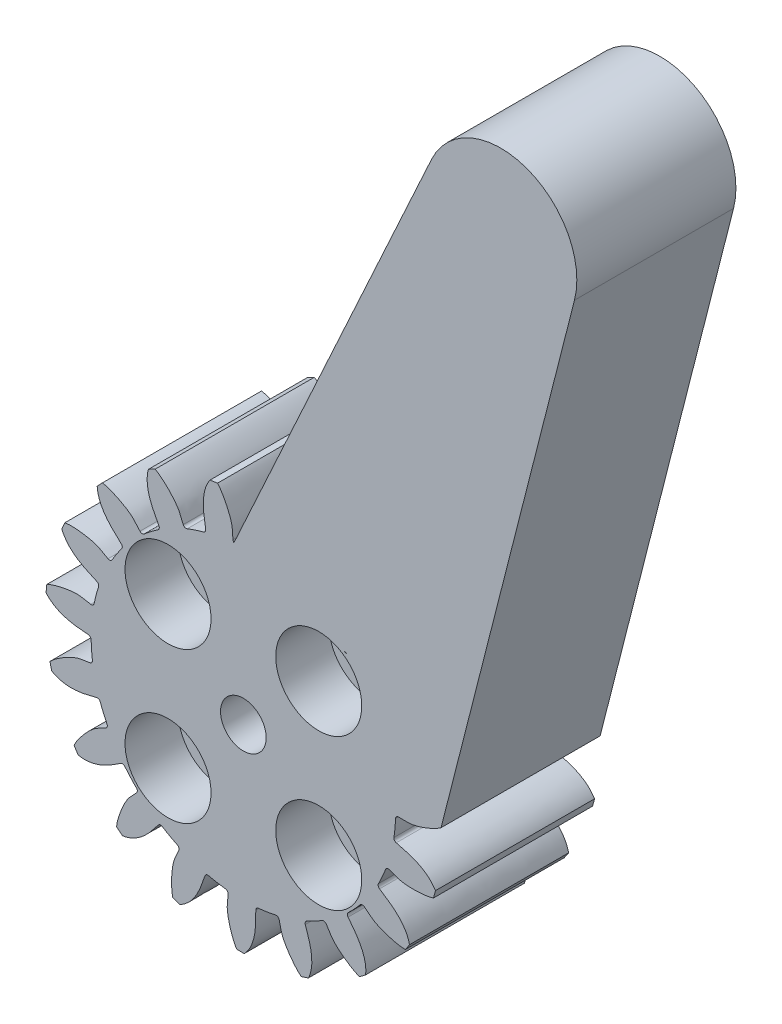
SolidWorks part; units mm, degrees
ref_plane "前视基准面" through (0, 0, 0) normal (0, 0, 1) x (1, 0, 0)
ref_plane "上视基准面" through (0, 0, 0) normal (0, 1, 0) x (1, 0, 0)
ref_plane "右视基准面" through (0, 0, 0) normal (1, 0, 0) x (0, 0, -1)
other "Configuration Table"
sketch "草图3" plane through (0, 0, 0) normal (0, 0, 1) x (1, 0, 0)
  circle A0 centre (0, 0) radius 13
  circle A1 centre (0, 0) radius 10
  dimension "D1" = 26
  dimension "D2" = 20
extrude "凸台-拉伸1" add sketch "草图3" along normal blind 4 contours A1 | A0 A1
sketch "草图6" plane through (0, 0, 4) normal (0, 0, 1) x (1, 0, 0)
  line L0 (0, 14.519) -> (0, -0.3622) construction
  line L5 (0, 0) -> (-1.6968, 12.8888) construction
  line L6 (-1.6968, 12.8888) -> (-1.8736, 14.2316)
  line L7 (-1.8736, 14.2316) -> (3.0009, 14.404)
  line L8 (3.0009, 14.404) -> (2.085, 12.8317)
  arc A0 (0.6559, 9.9785) -> (-0.4764, 9.9886) centre (0, 0) ccw
  circle A1 centre (0, 0) radius 13 construction
  arc A2 (0.6559, 9.9785) -> (0.8668, 10.1484) centre (0.669, 10.178) ccw
  arc A3 (-0.6854, 10.1744) -> (-0.4764, 9.9886) centre (-0.4859, 10.1884) ccw
  spline S0 degree 3 poles (-1.6968, 12.8888) (-1.3404, 12.4914) (-0.7219, 11.2236) (-0.7215, 10.6885) (-0.6854, 10.1744) knots 0 0 0 0 0.644244 0.940775 0.940775 0.940775 0.940775
  spline S1 degree 3 poles (2.085, 12.8317) (1.4718, 12.3854) (1.0735, 11.4242) (0.9081, 10.424) (0.8668, 10.1484) knots 0 0 0 0 0.67612 0.940775 0.940775 0.940775 0.940775
  dimension "D1" = 20
  dimension "D2" = 0.2
  dimension "D3" = 7.5
extrude "切除-拉伸2" cut sketch "草图6" against normal through all both
pattern_circular "阵列(圆周)4" count 19 over 360 about axis through (0, 0, 4) along (0, 0, 1) of "切除-拉伸2"
ref_plane "基准面3" through (0, 0, 2) normal (0, 0, 1) x (1, 0, 0)
sketch "草图8" plane through (0, 0, 0) normal (0, 0, -1) x (-1, 0, 0)
  line L1 (-4.9497, -4.9497) -> (4.9497, -4.9497) construction
  line L2 (-4.9497, -4.9497) -> (-4.9497, 4.9497) construction
  line L3 (-4.9497, 4.9497) -> (4.9497, 4.9497) construction
  line L4 (4.9497, -4.9497) -> (4.9497, 4.9497) construction
  line L5 (-4.9497, -4.9497) -> (4.9497, 4.9497) construction
  line L6 (-4.9497, 4.9497) -> (4.9497, -4.9497) construction
  circle A0 centre (0, 0) radius 1.5
  circle A1 centre (-4.9497, 4.9497) radius 1.5
  circle A2 centre (-4.9497, -4.9497) radius 1.5
  circle A3 centre (4.9497, -4.9497) radius 1.5
  circle A4 centre (4.9497, 4.9497) radius 1.5
  dimension "D1" = 3
  dimension "D3" = 3
  dimension "D4" = 3
  dimension "D5" = 3
  dimension "D6" = 3
  dimension "D2" = 14
extrude "切除-拉伸4" cut sketch "草图8" against normal through all both and the other way through all
sketch "草图13" plane through (0, 0, 0) normal (0, 0, -1) x (-1, 0, 0)
  circle A0 centre (-4.9497, -4.9497) radius 1.5 construction
  circle A1 centre (4.9497, -4.9497) radius 1.5 construction
  circle A2 centre (4.9497, 4.9497) radius 1.5 construction
  circle A3 centre (0, 0) radius 1.5 construction
  circle A4 centre (-4.9497, 4.9497) radius 1.5 construction
  circle A5 centre (-4.9497, -4.9497) radius 1.5
  circle A6 centre (4.9497, -4.9497) radius 1.5
  circle A7 centre (4.9497, 4.9497) radius 1.5
  circle A8 centre (0, 0) radius 1.5
  circle A9 centre (-4.9497, 4.9497) radius 1.5
  arc A61 (2.4754, 9.88) -> (2.6197, 9.6508) centre (2.6721, 9.8438) ccw
  arc A62 (2.4754, 9.88) -> (2.6197, 9.6508) centre (2.6721, 9.8438) ccw
  arc A63 (0.4764, 9.9886) -> (0.6854, 10.1744) centre (0.4859, 10.1884) ccw
  arc A64 (-11.8827, 5.2728) -> (-12.0778, 4.8089) centre (0, 0) ccw
  arc A65 (-12.9509, 1.1288) -> (-12.9849, 0.6267) centre (0, 0) ccw
  arc A66 (-9.9939, -0.3501) -> (-10.1963, -0.1571) centre (-10.1937, -0.3571) ccw
  arc A67 (-9.9939, -0.3501) -> (-9.8902, -1.4776) centre (0, 0) ccw
  arc A68 (-10.0421, -1.7019) -> (-9.8902, -1.4776) centre (-10.088, -1.5072) ccw
  arc A69 (-12.6157, -3.1375) -> (-12.4848, -3.6234) centre (0, 0) ccw
  arc A70 (-9.3387, -3.5761) -> (-9.5928, -3.4593) centre (-9.5255, -3.6476) ccw
  arc A71 (-9.3387, -3.5761) -> (-8.8746, -4.6089) centre (0, 0) ccw
  arc A72 (-8.9454, -4.8703) -> (-8.8746, -4.6089) centre (-9.052, -4.7011) ccw
  arc A73 (-10.9134, -7.0638) -> (-10.6318, -7.4809) centre (0, 0) ccw
  arc A74 (-7.6715, -6.4146) -> (-7.9498, -6.3867) centre (-7.825, -6.5429) ccw
  arc A75 (-7.6715, -6.4146) -> (-6.8972, -7.2408) centre (0, 0) ccw
  arc A76 (-6.8794, -7.511) -> (-6.8972, -7.2408) centre (-7.0351, -7.3856) ccw
  arc A77 (-8.0285, -10.2247) -> (-7.6267, -10.5277) centre (0, 0) ccw
  arc A78 (-5.1731, -8.558) -> (-5.4453, -8.6219) centre (-5.2765, -8.7292) ccw
  arc A79 (-5.1731, -8.558) -> (-4.1724, -9.088) centre (0, 0) ccw
  arc A80 (-4.0678, -9.3378) -> (-4.1724, -9.088) centre (-4.2559, -9.2697) ccw
  arc A81 (-4.2735, -12.2775) -> (-3.7951, -12.4337) centre (0, 0) ccw
  arc A82 (-2.114, -9.774) -> (-2.3508, -9.9228) centre (-2.1563, -9.9695) ccw
  arc A83 (-2.114, -9.774) -> (-0.9955, -9.9503) centre (0, 0) ccw
  arc A84 (-0.8154, -10.1526) -> (-0.9955, -9.9503) centre (-1.0154, -10.1493) ccw
  arc A85 (-0.0555, -12.9999) -> (0.4477, -12.9923) centre (0, 0) ccw
  arc A86 (1.1742, -9.9308) -> (0.9986, -10.1485) centre (1.1976, -10.1294) ccw
  arc A87 (1.1742, -9.9308) -> (2.2893, -9.7344) centre (0, 0) ccw
  arc A88 (2.5253, -9.8673) -> (2.2893, -9.7344) centre (2.3351, -9.9291) ccw
  arc A89 (4.1686, -12.3135) -> (4.6421, -12.143) centre (0, 0) ccw
  arc A90 (4.3351, -9.0115) -> (4.2397, -9.2744) centre (4.4218, -9.1917) ccw
  arc A91 (4.3351, -9.0115) -> (5.326, -8.4636) centre (0, 0) ccw
  arc A92 (5.5924, -8.5127) -> (5.326, -8.4636) centre (5.4326, -8.6329) ccw
  arc A93 (7.9409, -10.2928) -> (8.3333, -9.9777) centre (0, 0) ccw
  arc A94 (7.0262, -7.1156) -> (7.0213, -7.3953) centre (7.1667, -7.2579) ccw
  arc A95 (7.0262, -7.1156) -> (7.7856, -6.2757) centre (0, 0) ccw
  arc A96 (8.0535, -6.2356) -> (7.7856, -6.2757) centre (7.9413, -6.4012) ccw
  arc A97 (10.8527, -7.1567) -> (11.1216, -6.7313) centre (0, 0) ccw
  arc A98 (8.956, -4.4487) -> (9.0421, -4.7147) centre (9.1351, -4.5376) ccw
  arc A99 (8.956, -4.4487) -> (9.4015, -3.4077) centre (0, 0) ccw
  arc A100 (9.6418, -3.2828) -> (9.4015, -3.4077) centre (9.5895, -3.4758) ccw
  arc A101 (12.5885, -3.2451) -> (12.7046, -2.7554) centre (0, 0) ccw
  arc A102 (9.9152, -1.2996) -> (10.0831, -1.5233) centre (10.1135, -1.3256) ccw
  arc A103 (9.9152, -1.2996) -> (9.9985, -0.1704) centre (0, 0) ccw
  arc A104 (10.1853, 0.0258) -> (9.9985, -0.1704) centre (10.1985, -0.1738) ccw
  arc A105 (12.9601, 1.0182) -> (12.9109, 1.5191) centre (0, 0) ccw
  arc A106 (9.7999, 1.9902) -> (10.0314, 1.8332) centre (9.9959, 2.03) ccw
  arc A107 (9.7999, 1.9902) -> (9.5121, 3.0854) centre (0, 0) ccw
  arc A108 (9.6251, 3.3315) -> (9.5121, 3.0854) centre (9.7024, 3.1471) ccw
  arc A109 (11.9272, 5.1712) -> (11.7181, 5.629) centre (0, 0) ccw
  arc A110 (8.6227, 5.0644) -> (8.8926, 4.9911) centre (8.7952, 5.1657) ccw
  arc A111 (8.6227, 5.0644) -> (7.9949, 6.0068) centre (0, 0) ccw
  arc A112 (8.0218, 6.2763) -> (7.9949, 6.0068) centre (8.1548, 6.1269) ccw
  arc A113 (9.6019, 8.7638) -> (9.2555, 9.1288) centre (0, 0) ccw
  arc A114 (6.5111, 7.5898) -> (6.7902, 7.608) centre (6.6413, 7.7416) ccw
  arc A115 (6.5111, 7.5898) -> (5.6113, 8.2773) centre (0, 0) ccw
  arc A116 (5.5493, 8.5409) -> (5.6113, 8.2773) centre (5.7236, 8.4428) ccw
  arc A117 (6.236, 11.4067) -> (5.7899, 11.6395) centre (0, 0) ccw
  arc A118 (3.6939, 9.2927) -> (3.9519, 9.4006) centre (3.7678, 9.4786) ccw
  arc A119 (3.6939, 9.2927) -> (2.6197, 9.6508) centre (0, 0) ccw
  arc A120 (2.1944, 12.8134) -> (1.6968, 12.8888) centre (0, 0) ccw
  arc A121 (0.4764, 9.9886) -> (0.6854, 10.1744) centre (0.4859, 10.1884) ccw
  arc A125 (-11.8827, 5.2728) -> (-12.0778, 4.8089) centre (0, 0) ccw
  arc A126 (-12.9509, 1.1288) -> (-12.9849, 0.6267) centre (0, 0) ccw
  arc A127 (-9.9939, -0.3501) -> (-10.1963, -0.1571) centre (-10.1937, -0.3571) ccw
  arc A128 (-9.9939, -0.3501) -> (-9.8902, -1.4776) centre (0, 0) ccw
  arc A129 (-10.0421, -1.7019) -> (-9.8902, -1.4776) centre (-10.088, -1.5072) ccw
  arc A130 (-12.6157, -3.1375) -> (-12.4848, -3.6234) centre (0, 0) ccw
  arc A131 (-9.3387, -3.5761) -> (-9.5928, -3.4593) centre (-9.5255, -3.6476) ccw
  arc A132 (-9.3387, -3.5761) -> (-8.8746, -4.6089) centre (0, 0) ccw
  arc A133 (-8.9454, -4.8703) -> (-8.8746, -4.6089) centre (-9.052, -4.7011) ccw
  arc A134 (-10.9134, -7.0638) -> (-10.6318, -7.4809) centre (0, 0) ccw
  arc A135 (-7.6715, -6.4146) -> (-7.9498, -6.3867) centre (-7.825, -6.5429) ccw
  arc A136 (-7.6715, -6.4146) -> (-6.8972, -7.2408) centre (0, 0) ccw
  arc A137 (-6.8794, -7.511) -> (-6.8972, -7.2408) centre (-7.0351, -7.3856) ccw
  arc A138 (-8.0285, -10.2247) -> (-7.6267, -10.5277) centre (0, 0) ccw
  arc A139 (-5.1731, -8.558) -> (-5.4453, -8.6219) centre (-5.2765, -8.7292) ccw
  arc A140 (-5.1731, -8.558) -> (-4.1724, -9.088) centre (0, 0) ccw
  arc A141 (-4.0678, -9.3378) -> (-4.1724, -9.088) centre (-4.2559, -9.2697) ccw
  arc A142 (-4.2735, -12.2775) -> (-3.7951, -12.4337) centre (0, 0) ccw
  arc A143 (-2.114, -9.774) -> (-2.3508, -9.9228) centre (-2.1563, -9.9695) ccw
  arc A144 (-2.114, -9.774) -> (-0.9955, -9.9503) centre (0, 0) ccw
  arc A145 (-0.8154, -10.1526) -> (-0.9955, -9.9503) centre (-1.0154, -10.1493) ccw
  arc A146 (-0.0555, -12.9999) -> (0.4477, -12.9923) centre (0, 0) ccw
  arc A147 (1.1742, -9.9308) -> (0.9986, -10.1485) centre (1.1976, -10.1294) ccw
  arc A148 (1.1742, -9.9308) -> (2.2893, -9.7344) centre (0, 0) ccw
  arc A149 (2.5253, -9.8673) -> (2.2893, -9.7344) centre (2.3351, -9.9291) ccw
  arc A150 (4.1686, -12.3135) -> (4.6421, -12.143) centre (0, 0) ccw
  arc A151 (4.3351, -9.0115) -> (4.2397, -9.2744) centre (4.4218, -9.1917) ccw
  arc A152 (4.3351, -9.0115) -> (5.326, -8.4636) centre (0, 0) ccw
  arc A153 (5.5924, -8.5127) -> (5.326, -8.4636) centre (5.4326, -8.6329) ccw
  arc A154 (7.9409, -10.2928) -> (8.3333, -9.9777) centre (0, 0) ccw
  arc A155 (7.0262, -7.1156) -> (7.0213, -7.3953) centre (7.1667, -7.2579) ccw
  arc A156 (7.0262, -7.1156) -> (7.7856, -6.2757) centre (0, 0) ccw
  arc A157 (8.0535, -6.2356) -> (7.7856, -6.2757) centre (7.9413, -6.4012) ccw
  arc A158 (10.8527, -7.1567) -> (11.1216, -6.7313) centre (0, 0) ccw
  arc A159 (8.956, -4.4487) -> (9.0421, -4.7147) centre (9.1351, -4.5376) ccw
  arc A160 (8.956, -4.4487) -> (9.4015, -3.4077) centre (0, 0) ccw
  arc A161 (9.6418, -3.2828) -> (9.4015, -3.4077) centre (9.5895, -3.4758) ccw
  arc A162 (12.5885, -3.2451) -> (12.7046, -2.7554) centre (0, 0) ccw
  arc A163 (9.9152, -1.2996) -> (10.0831, -1.5233) centre (10.1135, -1.3256) ccw
  arc A164 (9.9152, -1.2996) -> (9.9985, -0.1704) centre (0, 0) ccw
  arc A165 (10.1853, 0.0258) -> (9.9985, -0.1704) centre (10.1985, -0.1738) ccw
  arc A166 (12.9601, 1.0182) -> (12.9109, 1.5191) centre (0, 0) ccw
  arc A167 (9.7999, 1.9902) -> (10.0314, 1.8332) centre (9.9959, 2.03) ccw
  arc A168 (9.7999, 1.9902) -> (9.5121, 3.0854) centre (0, 0) ccw
  arc A169 (9.6251, 3.3315) -> (9.5121, 3.0854) centre (9.7024, 3.1471) ccw
  arc A170 (11.9272, 5.1712) -> (11.7181, 5.629) centre (0, 0) ccw
  arc A171 (8.6227, 5.0644) -> (8.8926, 4.9911) centre (8.7952, 5.1657) ccw
  arc A172 (8.6227, 5.0644) -> (7.9949, 6.0068) centre (0, 0) ccw
  arc A173 (8.0218, 6.2763) -> (7.9949, 6.0068) centre (8.1548, 6.1269) ccw
  arc A174 (9.6019, 8.7638) -> (9.2555, 9.1288) centre (0, 0) ccw
  arc A175 (6.5111, 7.5898) -> (6.7902, 7.608) centre (6.6413, 7.7416) ccw
  arc A176 (6.5111, 7.5898) -> (5.6113, 8.2773) centre (0, 0) ccw
  arc A177 (5.5493, 8.5409) -> (5.6113, 8.2773) centre (5.7236, 8.4428) ccw
  arc A178 (6.236, 11.4067) -> (5.7899, 11.6395) centre (0, 0) ccw
  arc A179 (3.6939, 9.2927) -> (3.9519, 9.4006) centre (3.7678, 9.4786) ccw
  arc A180 (3.6939, 9.2927) -> (2.6197, 9.6508) centre (0, 0) ccw
  arc A181 (2.1944, 12.8134) -> (1.6968, 12.8888) centre (0, 0) ccw
  arc A192 (0.4764, 9.9886) -> (-0.6559, 9.9785) centre (0, 0) ccw
  arc A193 (0.4764, 9.9886) -> (-0.6559, 9.9785) centre (0, 0) ccw
  arc A210 (-0.8668, 10.1484) -> (-0.6559, 9.9785) centre (-0.669, 10.178) ccw
  arc A211 (-0.8668, 10.1484) -> (-0.6559, 9.9785) centre (-0.669, 10.178) ccw
  arc A212 (-2.085, 12.8317) -> (-2.5801, 12.7414) centre (0, 0) ccw
  arc A213 (-2.085, 12.8317) -> (-2.5801, 12.7414) centre (0, 0) ccw
  arc A214 (-2.7927, 9.6021) -> (-2.6553, 9.8457) centre (-2.8486, 9.7942) ccw
  arc A215 (-2.7927, 9.6021) -> (-2.6553, 9.8457) centre (-2.8486, 9.7942) ccw
  arc A216 (-2.7927, 9.6021) -> (-3.8603, 9.2248) centre (0, 0) ccw
  arc A217 (-2.7927, 9.6021) -> (-3.8603, 9.2248) centre (0, 0) ccw
  arc A218 (-4.115, 9.3171) -> (-3.8603, 9.2248) centre (-3.9375, 9.4093) ccw
  arc A219 (-4.115, 9.3171) -> (-3.8603, 9.2248) centre (-3.9375, 9.4093) ccw
  arc A220 (-6.1385, 11.4595) -> (-6.5774, 11.2133) centre (0, 0) ccw
  arc A221 (-6.1385, 11.4595) -> (-6.5774, 11.2133) centre (0, 0) ccw
  arc A222 (-5.7592, 8.1751) -> (-5.7084, 8.4501) centre (-5.8744, 8.3386) ccw
  arc A223 (-5.7592, 8.1751) -> (-5.7084, 8.4501) centre (-5.8744, 8.3386) ccw
  arc A224 (-5.7592, 8.1751) -> (-6.6465, 7.4716) centre (0, 0) ccw
  arc A225 (-5.7592, 8.1751) -> (-6.6465, 7.4716) centre (0, 0) ccw
  arc A226 (-6.9173, 7.4761) -> (-6.6465, 7.4716) centre (-6.7794, 7.621) ccw
  arc A227 (-6.9173, 7.4761) -> (-6.6465, 7.4716) centre (-6.7794, 7.621) ccw
  arc A228 (-9.5268, 8.8454) -> (-9.862, 8.47) centre (0, 0) ccw
  arc A229 (-9.5268, 8.8454) -> (-9.862, 8.47) centre (0, 0) ccw
  arc A230 (-8.1016, 5.8621) -> (-8.1428, 6.1387) centre (-8.2636, 5.9793) ccw
  arc A231 (-8.1016, 5.8621) -> (-8.1428, 6.1387) centre (-8.2636, 5.9793) ccw
  arc A232 (-8.1016, 5.8621) -> (-8.7124, 4.9086) centre (0, 0) ccw
  arc A233 (-8.1016, 5.8621) -> (-8.7124, 4.9086) centre (0, 0) ccw
  arc A234 (-8.97, 4.825) -> (-8.7124, 4.9086) centre (-8.8866, 5.0068) ccw
  arc A235 (-8.97, 4.825) -> (-8.7124, 4.9086) centre (-8.8866, 5.0068) ccw
  arc A236 (-9.566, 2.9139) -> (-9.6948, 3.1621) centre (-9.7574, 2.9722) ccw
  arc A237 (-9.566, 2.9139) -> (-9.6948, 3.1621) centre (-9.7574, 2.9722) ccw
  arc A238 (-9.566, 2.9139) -> (-9.8341, 1.8138) centre (0, 0) ccw
  arc A239 (-9.566, 2.9139) -> (-9.8341, 1.8138) centre (0, 0) ccw
  arc A240 (-10.0506, 1.651) -> (-9.8341, 1.8138) centre (-10.0308, 1.85) ccw
  arc A241 (-10.0506, 1.651) -> (-9.8341, 1.8138) centre (-10.0308, 1.85) ccw
  spline S32 degree 3 poles (-52.3193, 2004.3279) (-1.9263, -49.9972) (9.5073, 46.1834) (-51.7459, -23.6861) (372.2744, -1957.0595) knots -13.323382 -13.323382 -13.323382 -13.323382 0.264655 12.747684 12.747684 12.747684 12.747684 only from (-8.97, 4.825) to (-11.8827, 5.2728)
  spline S33 degree 3 poles (1606.9386, -1169.156) (-72.321, 78.5685) (14.3828, -33.7035) (-18.9668, 21.4939) (1783.7658, -881.8395) knots -8.147056 -8.147056 -8.147056 -8.147056 0.644244 5.645993 5.645993 5.645993 5.645993 only from (-12.0778, 4.8089) to (-9.6948, 3.1621)
  spline S34 degree 3 poles (-700.2887, 1878.7399) (14.4121, -47.9136) (-6.0036, 46.7681) (-41.2513, -39.2046) (987.5597, -1730.1433) knots -13.323382 -13.323382 -13.323382 -13.323382 0.264655 12.747684 12.747684 12.747684 12.747684 only from (-10.0506, 1.651) to (-12.9509, 1.1288)
  spline S35 degree 3 poles (1899.4945, -584.0357) (-93.9136, 50.8288) (24.547, -27.2073) (-24.9182, 14.1708) (1973.4493, -254.8711) knots -8.147056 -8.147056 -8.147056 -8.147056 0.644244 5.645993 5.645993 5.645993 5.645993 only from (-12.9849, 0.6267) to (-10.1963, -0.1571)
  spline S36 degree 3 poles (-1272.3709, 1549.5612) (29.1888, -40.6379) (-20.8639, 42.2847) (-26.2865, -50.4746) (1495.8276, -1315.7393) knots -13.323382 -13.323382 -13.323382 -13.323382 0.264655 12.747684 12.747684 12.747684 12.747684 only from (-10.0421, -1.7019) to (-12.6157, -3.1375)
  spline S37 degree 3 poles (1986.2108, 64.3738) (-105.3292, 17.5811) (32.0512, -17.7627) (-28.1693, 5.3121) (1949.2789, 399.7164) knots -8.147056 -8.147056 -8.147056 -8.147056 0.644244 5.645993 5.645993 5.645993 5.645993 only from (-12.4848, -3.6234) to (-9.5928, -3.4593)
  spline S38 degree 3 poles (-1706.5721, 1052.4635) (40.8024, -28.9585) (-33.4632, 33.2192) (-8.4731, -56.275) (1841.9994, -758.7545) knots -13.323382 -13.323382 -13.323382 -13.323382 0.264655 12.747684 12.747684 12.747684 12.747684 only from (-8.9454, -4.8703) to (-10.9134, -7.0638)
  spline S39 degree 3 poles (1857.6903, 705.8074) (-105.3307, -17.5719) (36.0821, -6.3933) (-28.3678, -4.1223) (1713.8739, 1010.9885) knots -8.147056 -8.147056 -8.147056 -8.147056 0.644244 5.645993 5.645993 5.645993 5.645993 only from (-10.6318, -7.4809) to (-7.9498, -6.3867)
  spline S40 degree 3 poles (-1955.8396, 441.3151) (47.9944, -14.1409) (-42.4363, 20.5538) (10.2584, -55.9771) (1988.562, -119.5468) knots -13.323382 -13.323382 -13.323382 -13.323382 0.264655 12.747684 12.747684 12.747684 12.747684 only from (-6.8794, -7.511) to (-8.0285, -10.2247)
  spline S41 degree 3 poles (1527.8602, 1270.7559) (-93.9181, -50.8206) (36.203, 5.6689) (-25.4922, -13.11) (1292.744, 1512.7043) knots -8.147056 -8.147056 -8.147056 -8.147056 0.644244 5.645993 5.645993 5.645993 5.645993 only from (-7.6267, -10.5277) to (-5.4453, -8.6219)
  spline S42 degree 3 poles (-1993.1616, -217.6567) (49.9855, 2.209) (-46.8108, 5.661) (27.8783, -49.6132) (1919.633, 532.6155) knots -13.323382 -13.323382 -13.323382 -13.323382 0.264655 12.747684 12.747684 12.747684 12.747684 only from (-4.0678, -9.3378) to (-4.2735, -12.2775)
  spline S43 degree 3 poles (1032.4628, 1697.9982) (-72.3279, -78.5622) (32.4007, 17.1169) (-19.8542, -20.6769) (731.5253, 1850.4951) knots -8.147056 -8.147056 -8.147056 -8.147056 0.644244 5.645993 5.645993 5.645993 5.645993 only from (-3.7951, -12.4337) to (-2.3508, -9.9228)
  spline S44 degree 3 poles (-1814.4936, -853.042) (46.5599, 18.3196) (-46.1126, -9.8451) (42.4772, -37.8729) (1642.682, 1127.0608) knots -13.323382 -13.323382 -13.323382 -13.323382 0.264655 12.747684 12.747684 12.747684 12.747684 only from (-0.8154, -10.1526) to (-0.0555, -12.9999)
  spline S45 degree 3 poles (425.182, 1941.2361) (-42.8999, -97.7903) (25.0873, 26.7099) (-12.0647, -26.0033) (91.0345, 1987.756) knots -8.147056 -8.147056 -8.147056 -8.147056 0.644244 5.645993 5.645993 5.645993 5.645993 only from (0.4477, -12.9923) to (0.9986, -10.1485)
  spline S46 degree 3 poles (-1439.1971, -1395.9869) (38.0888, 32.4449) (-40.4174, -24.2844) (52.473, -22.0286) (1187.7209, 1599.3715) knots -13.323382 -13.323382 -13.323382 -13.323382 0.264655 12.747684 12.747684 12.747684 12.747684 only from (2.5253, -9.8673) to (4.1686, -12.3135)
  spline S47 degree 3 poles (-228.1739, 1974.1109) (-8.823, -106.4213) (15.0553, 33.4085) (-2.9677, -28.5117) (-559.3213, 1909.6128) knots -8.147056 -8.147056 -8.147056 -8.147056 0.644244 5.645993 5.645993 5.645993 5.645993 only from (4.6421, -12.143) to (4.2397, -9.2744)
  spline S48 degree 3 poles (-907.9412, -1787.655) (25.4902, 43.0544) (-30.3423, -36.0921) (56.7825, -3.797) (604.0518, 1898.3655) knots -13.323382 -13.323382 -13.323382 -13.323382 0.264655 12.747684 12.747684 12.747684 12.747684 only from (5.5924, -8.5127) to (7.9409, -10.2928)
  spline S49 degree 3 poles (-856.8036, 1793.0602) (26.21, -103.5199) (3.3918, 36.4868) (6.4508, -27.9305) (-1149.066, 1624.5333) knots -8.147056 -8.147056 -8.147056 -8.147056 0.644244 5.645993 5.645993 5.645993 5.645993 only from (8.3333, -9.9777) to (7.0213, -7.3953)
  spline S50 degree 3 poles (-278.2958, -1985.603) (10.1293, 48.9982) (-16.9792, -43.9887) (54.9388, 14.8459) (-45.0756, 1991.6421) knots -13.323382 -13.323382 -13.323382 -13.323382 0.264655 12.747684 12.747684 12.747684 12.747684 only from (8.0535, -6.2356) to (10.8527, -7.1567)
  spline S51 degree 3 poles (-1392.5853, 1417.7036) (58.4027, -89.4005) (-8.6392, 35.6112) (15.1703, -24.3226) (-1614.2916, 1163.4105) knots -8.147056 -8.147056 -8.147056 -8.147056 0.644244 5.645993 5.645993 5.645993 5.645993 only from (11.1216, -6.7313) to (9.0421, -4.7147)
  spline S52 degree 3 poles (381.5072, -1968.38) (-6.3292, 49.6323) (-1.7761, -47.1184) (47.1416, 31.8801) (-689.3184, 1869.0934) knots -13.323382 -13.323382 -13.323382 -13.323382 0.264655 12.747684 12.747684 12.747684 12.747684 only from (9.6418, -3.2828) to (12.5885, -3.2451)
  spline S53 degree 3 poles (-1777.4588, 888.7168) (84.2666, -65.5932) (-19.734, 30.8765) (22.2459, -18.0789) (-1904.5836, 576.2141) knots -8.147056 -8.147056 -8.147056 -8.147056 0.644244 5.645993 5.645993 5.645993 5.645993 only from (12.7046, -2.7554) to (10.0831, -1.5233)
  spline S54 degree 3 poles (999.9681, -1737.8526) (-22.1019, 44.888) (13.6195, -45.1421) (34.2358, 45.4596) (-1258.8629, 1543.9995) knots -13.323382 -13.323382 -13.323382 -13.323382 0.264655 12.747684 12.747684 12.747684 12.747684 only from (10.1853, 0.0258) to (12.9601, 1.0182)
  spline S55 degree 3 poles (-1969.717, 263.4237) (100.9989, -34.6779) (-28.6904, 22.7959) (26.9107, -9.8761) (-1988.4844, -73.424) knots -8.147056 -8.147056 -8.147056 -8.147056 0.644244 5.645993 5.645993 5.645993 5.645993 only from (12.9109, 1.5191) to (10.0314, 1.8332)
  spline S56 degree 3 poles (1510.0669, -1319.0018) (-35.4795, 35.2794) (27.5391, -38.274) (17.6201, 54.1128) (-1691.99, 1051.5892) knots -13.323382 -13.323382 -13.323382 -13.323382 0.264655 12.747684 12.747684 12.747684 12.747684 only from (9.6251, 3.3315) to (11.9272, 5.1712)
  spline S57 degree 3 poles (-1948.5259, -390.4154) (106.7864, -0.0046) (-34.5377, 12.245) (28.6594, -0.6031) (-1856.9021, -715.1055) knots -8.147056 -8.147056 -8.147056 -8.147056 0.644244 5.645993 5.645993 5.645993 5.645993 only from (11.7181, 5.629) to (8.8926, 4.9911)
  spline S58 degree 3 poles (1856.5265, -757.2168) (-45.0123, 21.8477) (38.4745, -27.2582) (-0.905, 56.9021) (-1941.7638, 445.2229) knots -13.323382 -13.323382 -13.323382 -13.323382 0.264655 12.747684 12.747684 12.747684 12.747684 only from (8.0218, 6.2763) to (9.6019, 8.7638)
  spline S59 degree 3 poles (-1716.1817, -1001.9469) (101.0019, 34.6691) (-36.6423, 0.3672) (27.3024, 8.7353) (-1524.0956, -1279.2943) knots -8.147056 -8.147056 -8.147056 -8.147056 0.644244 5.645993 5.645993 5.645993 5.645993 only from (9.2555, 9.1288) to (6.7902, 7.608)
  spline S60 degree 3 poles (2001.8026, -113.3755) (-49.6673, 6.0485) (45.2406, -13.2886) (-19.332, 53.5251) (-1981.1173, -209.3902) knots -13.323382 -13.323382 -13.323382 -13.323382 0.264655 12.747684 12.747684 12.747684 12.747684 only from (5.5493, 8.5409) to (6.236, 11.4067)
  spline S61 degree 3 poles (-1297.8626, -1504.902) (84.2723, 65.5859) (-34.7761, -11.5504) (22.9867, 17.127) (-1026.1297, -1704.8516) knots -8.147056 -8.147056 -8.147056 -8.147056 0.644244 5.645993 5.645993 5.645993 5.645993 only from (5.7899, 11.6395) to (3.9519, 9.4006)
  spline S62 degree 3 poles (1930.1524, 542.7517) (-48.9401, -10.4062) (47.1042, 2.121) (-35.6642, 44.3479) (-1805.7861, -841.3126) knots -13.323382 -13.323382 -13.323382 -13.323382 0.264655 12.747684 12.747684 12.747684 12.747684 only from (2.4754, 9.88) to (2.1944, 12.8134)
  spline S64 degree 3 poles (-8.97, 4.825) (-9.2233, 4.9412) (-10.1511, 5.3497) (-11.1736, 5.5421) (-11.8827, 5.2728) knots 0 0 0 0 0.264655 0.940775 0.940775 0.940775 0.940775
  spline S65 degree 3 poles (-12.0778, 4.8089) (-11.7801, 4.3658) (-10.7029, 3.455) (-10.1843, 3.3233) (-9.6948, 3.1621) knots 0 0 0 0 0.644244 0.940775 0.940775 0.940775 0.940775
  spline S66 degree 3 poles (-10.0506, 1.651) (-10.328, 1.6786) (-11.3382, 1.7638) (-12.3677, 1.6137) (-12.9509, 1.1288) knots 0 0 0 0 0.264655 0.940775 0.940775 0.940775 0.940775
  spline S67 degree 3 poles (-12.9849, 0.6267) (-12.5594, 0.3043) (-11.2449, -0.2074) (-10.7115, -0.1636) (-10.1963, -0.1571) knots 0 0 0 0 0.644244 0.940775 0.940775 0.940775 0.940775
  spline S68 degree 3 poles (-10.0421, -1.7019) (-10.3134, -1.7658) (-11.2966, -2.0133) (-12.2216, -2.4895) (-12.6157, -3.1375) knots 0 0 0 0 0.264655 0.940775 0.940775 0.940775 0.940775
  spline S69 degree 3 poles (-12.4848, -3.6234) (-11.9777, -3.7902) (-10.5682, -3.8474) (-10.078, -3.6328) (-9.5928, -3.4593) knots 0 0 0 0 0.644244 0.940775 0.940775 0.940775 0.940775
  spline S70 degree 3 poles (-8.9454, -4.8703) (-9.1813, -5.0189) (-10.0308, -5.5722) (-10.751, -6.323) (-10.9134, -7.0638) knots 0 0 0 0 0.264655 0.940775 0.940775 0.940775 0.940775
  spline S71 degree 3 poles (-10.6318, -7.4809) (-10.098, -7.474) (-8.7464, -7.0704) (-8.3524, -6.7083) (-7.9498, -6.3867) knots 0 0 0 0 0.644244 0.940775 0.940775 0.940775 0.940775
  spline S72 degree 3 poles (-6.8794, -7.511) (-7.0542, -7.7281) (-7.678, -8.5272) (-8.1155, -9.4712) (-8.0285, -10.2247) knots 0 0 0 0 0.264655 0.940775 0.940775 0.940775 0.940775
  spline S73 degree 3 poles (-7.6267, -10.5277) (-7.1241, -10.3479) (-5.9767, -9.5273) (-5.7217, -9.0568) (-5.4453, -8.6219) knots 0 0 0 0 0.644244 0.940775 0.940775 0.940775 0.940775
  spline S74 degree 3 poles (-4.0678, -9.3378) (-4.1626, -9.5998) (-4.4932, -10.5582) (-4.6004, -11.5931) (-4.2735, -12.2775) knots 0 0 0 0 0.264655 0.940775 0.940775 0.940775 0.940775
  spline S75 degree 3 poles (-3.7951, -12.4337) (-3.3781, -12.1004) (-2.5593, -10.9517) (-2.4709, -10.4239) (-2.3508, -9.9228) knots 0 0 0 0 0.644244 0.940775 0.940775 0.940775 0.940775
  spline S76 degree 3 poles (-0.8154, -10.1526) (-0.82, -10.4313) (-0.8215, -11.4451) (-0.5869, -12.4587) (-0.0555, -12.9999) knots 0 0 0 0 0.264655 0.940775 0.940775 0.940775 0.940775
  spline S77 degree 3 poles (0.4477, -12.9923) (0.7339, -12.5416) (1.1353, -11.1893) (1.0476, -10.6614) (0.9986, -10.1485) knots 0 0 0 0 0.644244 0.940775 0.940775 0.940775 0.940775
  spline S78 degree 3 poles (2.5253, -9.8673) (2.6114, -10.1324) (2.9393, -11.0917) (3.4902, -11.9742) (4.1686, -12.3135) knots 0 0 0 0 0.264655 0.940775 0.940775 0.940775 0.940775
  spline S79 degree 3 poles (4.6421, -12.143) (4.7664, -11.6238) (4.707, -10.2144) (4.4526, -9.7436) (4.2397, -9.2744) knots 0 0 0 0 0.644244 0.940775 0.940775 0.940775 0.940775
  spline S80 degree 3 poles (5.5924, -8.5127) (5.7599, -8.7354) (6.3815, -9.5364) (7.1892, -10.1922) (7.9409, -10.2928) knots 0 0 0 0 0.264655 0.940775 0.940775 0.940775 0.940775
  spline S81 degree 3 poles (8.3333, -9.9777) (8.2824, -9.4463) (7.7686, -8.1326) (7.3751, -7.7699) (7.0213, -7.3953) knots 0 0 0 0 0.644244 0.940775 0.940775 0.940775 0.940775
  spline S82 degree 3 poles (8.0535, -6.2356) (8.2842, -6.3919) (9.1322, -6.9476) (10.109, -7.3056) (10.8527, -7.1567) knots 0 0 0 0 0.264655 0.940775 0.940775 0.940775 0.940775
  spline S83 degree 3 poles (11.1216, -6.7313) (10.9008, -6.2452) (9.9883, -5.1695) (9.4984, -4.9542) (9.0421, -4.7147) knots 0 0 0 0 0.644244 0.940775 0.940775 0.940775 0.940775
  spline S84 degree 3 poles (9.6418, -3.2828) (9.9108, -3.3557) (10.8932, -3.6059) (11.9334, -3.6274) (12.5885, -3.2451) knots 0 0 0 0 0.264655 0.940775 0.940775 0.940775 0.940775
  spline S85 degree 3 poles (12.7046, -2.7554) (12.338, -2.3673) (11.1256, -1.6462) (10.5924, -1.6017) (10.0831, -1.5233) knots 0 0 0 0 0.644244 0.940775 0.940775 0.940775 0.940775
  spline S86 degree 3 poles (10.1853, 0.0258) (10.4634, 0.0442) (11.4739, 0.1265) (12.4646, 0.4439) (12.9601, 1.0182) knots 0 0 0 0 0.264655 0.940775 0.940775 0.940775 0.940775
  spline S87 degree 3 poles (12.9109, 1.5191) (12.4382, 1.7671) (11.0573, 2.0555) (10.5385, 1.9245) (10.0314, 1.8332) knots 0 0 0 0 0.644244 0.940775 0.940775 0.940775 0.940775
  spline S88 degree 3 poles (9.6251, 3.3315) (9.8821, 3.4392) (10.8111, 3.8452) (11.6451, 4.4672) (11.9272, 5.1712) knots 0 0 0 0 0.264655 0.940775 0.940775 0.940775 0.940775
  spline S89 degree 3 poles (11.7181, 5.629) (11.1905, 5.71) (9.7908, 5.5344) (9.3426, 5.242) (8.8926, 4.9911) knots 0 0 0 0 0.644244 0.940775 0.940775 0.940775 0.940775
  spline S90 degree 3 poles (8.0218, 6.2763) (8.23, 6.4616) (8.9768, 7.1472) (9.5637, 8.0063) (9.6019, 8.7638) knots 0 0 0 0 0.264655 0.940775 0.940775 0.940775 0.940775
  spline S91 degree 3 poles (9.2555, 9.1288) (8.7301, 9.0342) (7.4633, 8.4136) (7.1343, 7.9916) (6.7902, 7.608) knots 0 0 0 0 0.644244 0.940775 0.940775 0.940775 0.940775
  spline S92 degree 3 poles (5.5493, 8.5409) (5.6859, 8.7838) (6.1697, 9.6747) (6.4459, 10.6778) (6.236, 11.4067) knots 0 0 0 0 0.264655 0.940775 0.940775 0.940775 0.940775
  spline S93 degree 3 poles (5.7899, 11.6395) (5.3237, 11.3793) (4.327, 10.3811) (4.1529, 9.8751) (3.9519, 9.4006) knots 0 0 0 0 0.644244 0.940775 0.940775 0.940775 0.940775
  spline S94 degree 3 poles (2.4754, 9.88) (2.5258, 10.1541) (2.6941, 11.1538) (2.6295, 12.1922) (2.1944, 12.8134) knots 0 0 0 0 0.264655 0.940775 0.940775 0.940775 0.940775
  spline S100 degree 3 poles (-360.0944, -919.3689) (38.5198, 63.8511) (-18.1905, -9.6389) (10.1838, 17.7194) (-203.4804, -968.7355) knots -6.415256 -6.415256 -6.415256 -6.415256 0.644244 4.622135 4.622135 4.622135 4.622135 only from (1.6968, 12.8888) to (0.6854, 10.1744)
  spline S101 degree 3 poles (1.6968, 12.8888) (1.3404, 12.4914) (0.7219, 11.2236) (0.7215, 10.6885) (0.6854, 10.1744) knots 0 0 0 0 0.644244 0.940775 0.940775 0.940775 0.940775
  spline S102 degree 3 poles (826.2136, 572.2298) (-26.7178, -17.0615) (27.4549, 14.6878) (-31.5613, 27.4612) (-731.3246, -671.4118) knots -10.597353 -10.597353 -10.597353 -10.597353 0.264655 10.147791 10.147791 10.147791 10.147791 only from (-0.8668, 10.1484) to (-2.085, 12.8317)
  spline S103 degree 3 poles (-0.8668, 10.1484) (-0.9081, 10.424) (-1.0735, 11.4242) (-1.4718, 12.3854) (-2.085, 12.8317) knots 0 0 0 0 0.264655 0.940775 0.940775 0.940775 0.940775
  spline S104 degree 3 poles (-42.0649, -986.4775) (15.7003, 72.8989) (-14.0751, -15.023) (3.8786, 20.066) (122.0926, -982.3168) knots -6.415256 -6.415256 -6.415256 -6.415256 0.644244 4.622135 4.622135 4.622135 4.622135 only from (-2.5801, 12.7414) to (-2.6553, 9.8457)
  spline S105 degree 3 poles (-2.5801, 12.7414) (-2.7882, 12.2498) (-2.9615, 10.8498) (-2.7881, 10.3436) (-2.6553, 9.8457) knots 0 0 0 0 0.644244 0.940775 0.940775 0.940775 0.940775
  spline S106 degree 3 poles (595.6444, 809.4959) (-19.7303, -24.8123) (21.1982, 22.8065) (-38.7678, 15.7254) (-473.6923, -872.4935) knots -10.597353 -10.597353 -10.597353 -10.597353 0.264655 10.147791 10.147791 10.147791 10.147791 only from (-4.115, 9.3171) to (-6.1385, 11.4595)
  spline S107 degree 3 poles (-4.115, 9.3171) (-4.2436, 9.5644) (-4.7248, 10.4567) (-5.4135, 11.2365) (-6.1385, 11.4595) knots 0 0 0 0 0.264655 0.940775 0.940775 0.940775 0.940775
  spline S108 degree 3 poles (280.523, -946.6858) (-8.8206, 74.0469) (-8.4345, -18.7792) (-2.847, 20.2381) (434.435, -889.4487) knots -6.415256 -6.415256 -6.415256 -6.415256 0.644244 4.622135 4.622135 4.622135 4.622135 only from (-6.5774, 11.2133) to (-5.7084, 8.4501)
  spline S109 degree 3 poles (-6.5774, 11.2133) (-6.6146, 10.6807) (-6.324, 9.3003) (-5.9956, 8.8778) (-5.7084, 8.4501) knots 0 0 0 0 0.644244 0.940775 0.940775 0.940775 0.940775
  spline S110 degree 3 poles (300.5278, 959.0406) (-10.6047, -29.8744) (12.6444, 28.4539) (-41.7733, 2.2854) (-164.7282, -979.0271) knots -10.597353 -10.597353 -10.597353 -10.597353 0.264655 10.147791 10.147791 10.147791 10.147791 only from (-6.9173, 7.4761) to (-9.5268, 8.8454)
  spline S111 degree 3 poles (-6.9173, 7.4761) (-7.1192, 7.6683) (-7.8641, 8.3559) (-8.7687, 8.8699) (-9.5268, 8.8454) knots 0 0 0 0 0.264655 0.940775 0.940775 0.940775 0.940775
  spline S112 degree 3 poles (572.7119, -804.3061) (-32.3857, 67.1708) (-1.8799, -20.5004) (-9.2641, 18.2171) (699.6997, -700.1951) knots -6.415256 -6.415256 -6.415256 -6.415256 0.644244 4.622135 4.622135 4.622135 4.622135 only from (-9.862, 8.47) to (-8.1428, 6.1387)
  spline S113 degree 3 poles (-9.862, 8.47) (-9.7242, 7.9542) (-9.0012, 6.743) (-8.5534, 6.45) (-8.1428, 6.1387) knots 0 0 0 0 0.644244 0.940775 0.940775 0.940775 0.940775
  dimension "D1" = 0
extrude "凸台-拉伸6" add sketch "草图13" along normal blind 6.45
sketch "草图14" plane through (0, 0, 4) normal (0, 0, 1) x (1, 0, 0)
  circle A0 centre (4.9497, -4.9497) radius 2.825
  circle A1 centre (-4.9497, -4.9497) radius 2.825
  circle A2 centre (-4.9497, 4.9497) radius 2.825
  circle A3 centre (4.9497, 4.9497) radius 2.825
  dimension "D1" = 5.65
extrude "切除-拉伸5" cut sketch "草图14" against normal blind 3.5
sketch "草图15" plane through (0, 0, -6.45) normal (0, 0, -1) x (-1, 0, 0)
  line L0 (0, 0) -> (23, 0) construction
  line L1 (11.5, 48.7376) -> (11.5, -48.7376) construction
  line L15 (0, 60) -> (0, 0) construction
  line L25 (0, 0) -> (-16.9047, 36.2523) construction
  line L26 (-21.7498, 35.0175) -> (-12.9849, 0.6267)
  line L27 (-12.3599, 38.3368) -> (0.6188, 10.0389)
  line L28 (-12.9849, 0.6267) -> (-10.8463, 1.0422)
  line L29 (-10.8463, 1.0422) -> (-9.5917, 1.6848)
  line L30 (-9.5917, 1.6848) -> (-8.9852, 3.5649)
  line L31 (-8.9852, 3.5649) -> (-8.123, 5.3872)
  line L32 (-8.123, 5.3872) -> (-7.2758, 7.1777)
  line L33 (-7.2758, 7.1777) -> (-5.4968, 8.0889)
  line L34 (-5.4968, 8.0889) -> (-4.3511, 8.6757)
  line L35 (-4.3511, 8.6757) -> (-2.3173, 9.7174)
  line L36 (-2.3173, 9.7174) -> (-0.6875, 9.7174)
  line L37 (-0.6875, 9.7174) -> (0.3528, 9.7174)
  line L38 (0.3528, 9.7174) -> (0.6188, 10.0389)
  arc A8 (-12.3599, 38.3368) -> (-21.7498, 35.0175) centre (-16.9047, 36.2523) ccw
  arc A9 (-12.9509, 1.1288) -> (-12.9849, 0.6267) centre (0, 0) ccw construction
  arc A10 (0.4764, 9.9886) -> (0.6854, 10.1744) centre (0.4859, 10.1884) ccw construction
  spline S0 degree 3 poles (-12.9849, 0.6267) (-12.5594, 0.3043) (-11.2449, -0.2074) (-10.7115, -0.1636) (-10.1963, -0.1571) knots 0 0 0 0 0.644244 0.940775 0.940775 0.940775 0.940775 construction
  point P7 (11.5, 0)
  dimension "D1" = 60
  dimension "D4" = 25
  dimension "D5" = 10
  dimension "D6" = 40
extrude "凸台-拉伸7" add sketch "草图15" against normal up to surface (10.45 mm away) up to face at (7.7747, 4.9497, 4)
